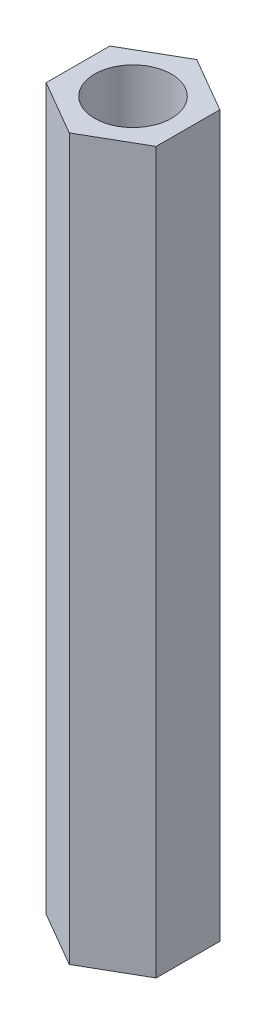
SolidWorks part; units mm, degrees
ref_plane "Front Plane" through (0, 0, 0) normal (0, 0, 1) x (1, 0, 0)
ref_plane "Top Plane" through (0, 0, 0) normal (0, 1, 0) x (1, 0, 0)
ref_plane "Right Plane" through (0, 0, 0) normal (1, 0, 0) x (0, 0, -1)
sketch "Sketch1" plane through (0, 0, 0) normal (0, 1, 0) x (1, 0, 0)
  line L1 (2.2922, -1.3298) -> (2.2977, 1.3202)
  line L2 (2.2977, 1.3202) -> (0.0055, 2.65)
  line L3 (0.0055, 2.65) -> (-2.2922, 1.3298)
  line L4 (-2.2922, 1.3298) -> (-2.2977, -1.3202)
  line L5 (-2.2977, -1.3202) -> (-0.0055, -2.65)
  line L6 (-0.0055, -2.65) -> (2.2922, -1.3298)
  circle A0 centre (0, 0) radius 2.295 construction
  dimension "D1" = 5.3
extrude "Boss-Extrude1" add sketch "Sketch1" along normal blind 30
sketch "Sketch2" plane through (0, 30, 0) normal (0, 1, 0) x (1, 0, 0)
  circle A0 centre (0, 0) radius 1.6
  dimension "D1" = 3.2
extrude "Cut-Extrude1" cut sketch "Sketch2" against normal blind 30
